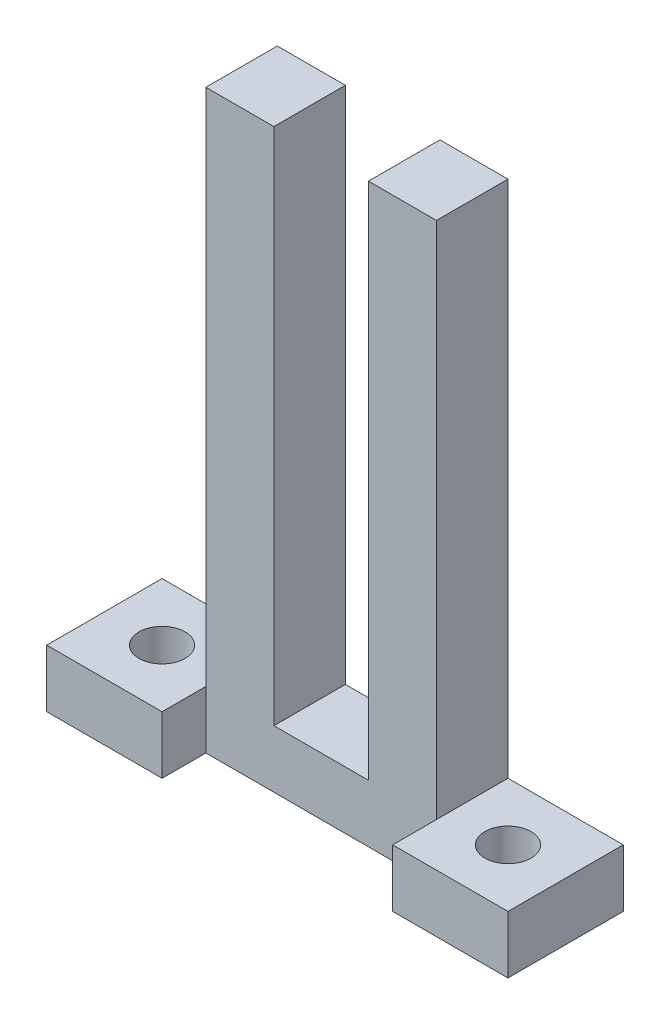
SolidWorks part; units mm, degrees
ref_plane "Спереди" through (0, 0, 0) normal (0, 0, 1) x (1, 0, 0)
ref_plane "Сверху" through (0, 0, 0) normal (0, 1, 0) x (1, 0, 0)
ref_plane "Справа" through (0, 0, 0) normal (1, 0, 0) x (0, 0, -1)
sketch "Эскиз2" plane through (0, 0, 0) normal (0, 1, 0) x (1, 0, 0)
  line L1 (0, 0) -> (5.9, 0)
  line L2 (0, 0) -> (0, 6.2)
  line L3 (0, 6.2) -> (5.9, 6.2)
  line L4 (5.9, 0) -> (5.9, 6.2)
  line L5 (14.1, 0) -> (20, 0)
  line L6 (14.1, 0) -> (14.1, 6.2)
  line L7 (14.1, 6.2) -> (20, 6.2)
  line L8 (20, 0) -> (20, 6.2)
  dimension "D1" = 6.2
  dimension "D2" = 20
  dimension "D3" = 8.2
extrude "Вытянуть1" add sketch "Эскиз2" along normal blind 50
sketch "Эскиз3" plane through (0, 0, 0) normal (0, 1, 0) x (1, 0, 0)
  line L0 (20, 6.2) -> (14.1, 6.2) construction
  line L1 (-10, 6.2) -> (30, 6.2)
  line L2 (-10, 6.2) -> (-10, 0)
  line L3 (-10, 0) -> (30, 0)
  line L4 (30, 6.2) -> (30, 0)
  point P7 (0, 6.2)
  point P8 (20, 6.2)
  point P10 (17.6484, 10.0183)
  dimension "D1" = 40
  dimension "D2" = 10
extrude "Вытянуть2" add sketch "Эскиз3" along normal blind 5
sketch "Эскиз4" plane through (0, 0, 0) normal (0, 0, 1) x (1, 0, 0)
  line L1 (-10, 5) -> (0, 5)
  line L2 (-10, 5) -> (-10, 0)
  line L3 (-10, 0) -> (0, 0)
  line L4 (0, 5) -> (0, 0)
  line L5 (20, 5) -> (30, 5)
  line L6 (20, 5) -> (20, 0)
  line L7 (20, 0) -> (30, 0)
  line L8 (30, 5) -> (30, 0)
extrude "Вытянуть3" add sketch "Эскиз4" along normal blind 3.8
sketch "Эскиз5" plane through (0, 5, 0) normal (0, 1, 0) x (1, 0, 0)
  line L0 (0, 6.2) -> (-10, 6.2) construction
  line L1 (-10, 6.2) -> (-10, -3.8) construction
  line L2 (30, 6.2) -> (20, 6.2) construction
  circle A0 centre (25, 1.2) radius 2
  circle A1 centre (-5, 1.2) radius 2
  point P0 (-5, 6.2)
  point P1 (-10, 1.2)
  point P4 (25, 6.2)
  dimension "D1" = 4
extrude "Вытянуть4" cut sketch "Эскиз5" against normal up to next
